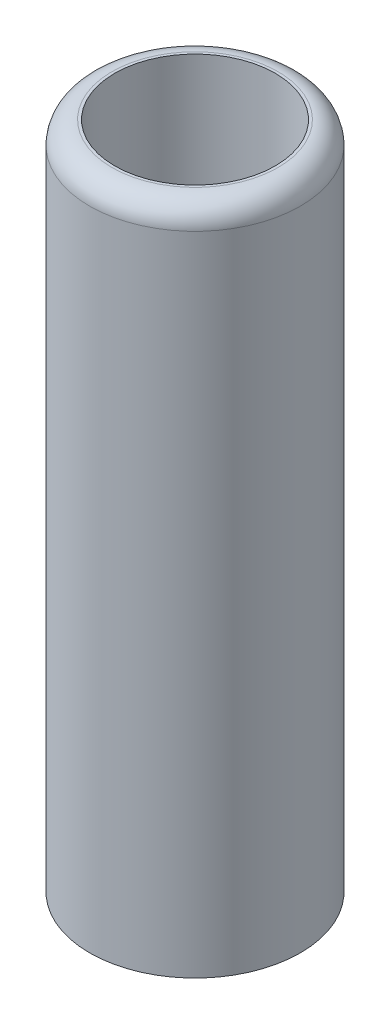
SolidWorks part; units mm, degrees
ref_plane "Front Plane" through (0, 0, 0) normal (0, 0, 1) x (1, 0, 0)
ref_plane "Top Plane" through (0, 0, 0) normal (0, 1, 0) x (1, 0, 0)
ref_plane "Right Plane" through (0, 0, 0) normal (1, 0, 0) x (0, 0, -1)
sketch "Sketch1" plane through (0, 0, 0) normal (0, 1, 0) x (1, 0, 0)
  circle A0 centre (0, 0) radius 9.45
  circle A1 centre (0, 0) radius 7.2
  dimension "D1" = 18.9
  dimension "D2" = 14.4
extrude "Boss-Extrude1" add sketch "Sketch1" along normal blind 60
fillet "Fillet1" radius 2 1 edges at (0, 60, 9.45)
ref_plane "Plane1" through (0, 10, 0) normal (0, 1, 0) x (1, 0, 0)
